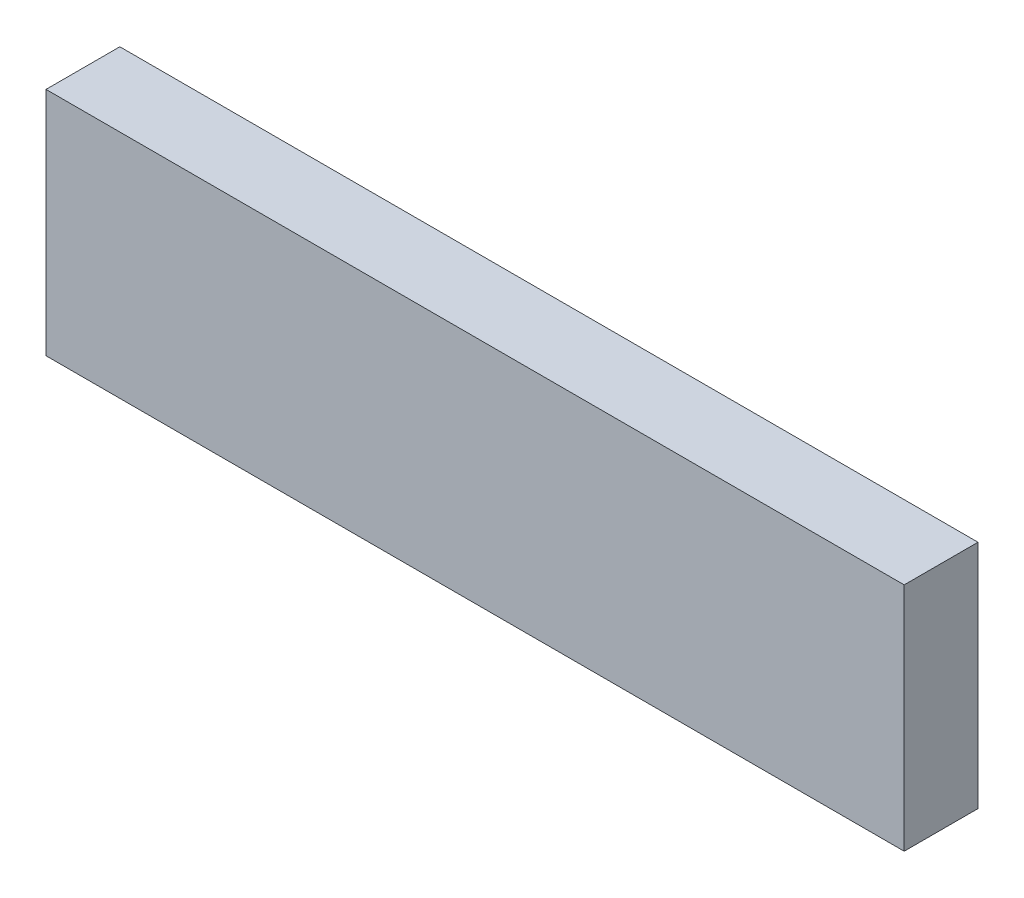
SolidWorks part; units mm, degrees
ref_plane "Plano frontal" through (0, 0, 0) normal (0, 0, 1) x (1, 0, 0)
ref_plane "Plano superior" through (0, 0, 0) normal (0, 1, 0) x (1, 0, 0)
ref_plane "Plano direito" through (0, 0, 0) normal (1, 0, 0) x (0, 0, -1)
sketch "Esboço_peso" plane through (0, 0, 0) normal (0, 0, 1) x (1, 0, 0)
  line L0 (0, 0) -> (93, 0)
  line L1 (93, 0) -> (93, 25)
  line L2 (93, 25) -> (0, 25)
  line L3 (0, 25) -> (0, 0)
  dimension "D1" = 25
  dimension "D2" = 93
extrude "Extrussão_peso" add sketch "Esboço_peso" along normal blind 8
